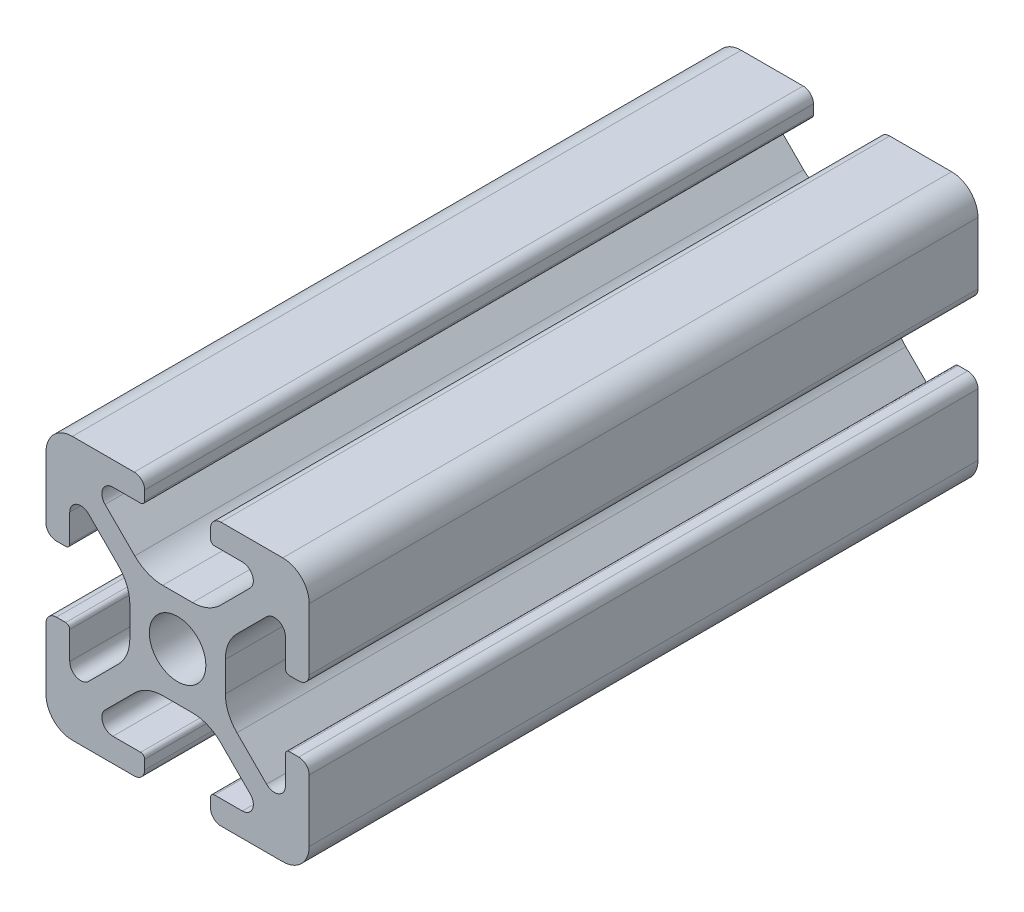
SolidWorks part; units mm, degrees
ref_plane "Front Plane" through (0, 0, 0) normal (0, 0, 1) x (1, 0, 0)
ref_plane "Top Plane" through (0, 0, 0) normal (0, 1, 0) x (1, 0, 0)
ref_plane "Right Plane" through (0, 0, 0) normal (1, 0, 0) x (0, 0, -1)
sketch "Sketch1" plane through (0, 0, 0) normal (0, 0, 1) x (1, 0, 0)
  line L2 (-9.9949, 7.9883) -> (-9.9949, 3.2893)
  line L3 (-7.9883, 9.9949) -> (-3.2893, 9.9949)
  line L4 (-2.5019, 9.2075) -> (-2.5019, 8.4963)
  line L5 (-2.8067, 8.1915) -> (-4.9149, 8.1915)
  line L6 (-5.5076, 6.7606) -> (-3.2528, 4.5058)
  line L7 (-6.7606, 5.5076) -> (-4.5058, 3.2528)
  line L8 (-8.1915, 4.9149) -> (-8.1915, 2.8067)
  line L9 (-8.4963, 2.5019) -> (-9.2075, 2.5019)
  line L11 (-1.1334, 3.6279) -> (1.1334, 3.6279)
  line L12 (-3.6279, 1.1334) -> (-3.6279, -1.1334)
  line L13 (8.4963, 2.5019) -> (9.2075, 2.5019)
  line L14 (8.1915, 4.9149) -> (8.1915, 2.8067)
  line L15 (9.9949, 7.9883) -> (9.9949, 3.2893)
  line L16 (7.9883, 9.9949) -> (3.2893, 9.9949)
  line L17 (2.5019, 9.2075) -> (2.5019, 8.4963)
  line L18 (2.8067, 8.1915) -> (4.9149, 8.1915)
  line L19 (3.6279, 1.1334) -> (3.6279, -1.1334)
  line L20 (5.5076, 6.7606) -> (3.2528, 4.5058)
  line L21 (6.7606, 5.5076) -> (4.5058, 3.2528)
  line L22 (-8.4963, -2.5019) -> (-9.2075, -2.5019)
  line L23 (-8.1915, -4.9149) -> (-8.1915, -2.8067)
  line L24 (-6.7606, -5.5076) -> (-4.5058, -3.2528)
  line L25 (-5.5076, -6.7606) -> (-3.2528, -4.5058)
  line L26 (-2.8067, -8.1915) -> (-4.9149, -8.1915)
  line L27 (-2.5019, -9.2075) -> (-2.5019, -8.4963)
  line L28 (-7.9883, -9.9949) -> (-3.2893, -9.9949)
  line L29 (-9.9949, -7.9883) -> (-9.9949, -3.2893)
  line L30 (9.9949, -7.9883) -> (9.9949, -3.2893)
  line L31 (7.9883, -9.9949) -> (3.2893, -9.9949)
  line L32 (2.5019, -9.2075) -> (2.5019, -8.4963)
  line L33 (2.8067, -8.1915) -> (4.9149, -8.1915)
  line L34 (5.5076, -6.7606) -> (3.2528, -4.5058)
  line L35 (6.7606, -5.5076) -> (4.5058, -3.2528)
  line L36 (8.1915, -4.9149) -> (8.1915, -2.8067)
  line L37 (8.4963, -2.5019) -> (9.2075, -2.5019)
  line L38 (-1.1334, -3.6279) -> (1.1334, -3.6279)
  circle A0 centre (0, 0) radius 2.1463
  arc A1 (-9.9949, 7.9883) -> (-7.9883, 9.9949) centre (-7.9883, 7.9883) cw
  arc A2 (-6.7606, 5.5076) -> (-8.1915, 4.9149) centre (-7.3533, 4.9149) ccw
  arc A3 (-4.9149, 8.1915) -> (-5.5076, 6.7606) centre (-4.9149, 7.3533) ccw
  arc A4 (-3.2893, 9.9949) -> (-2.5019, 9.2075) centre (-3.2893, 9.2075) cw
  arc A5 (-9.9949, 3.2893) -> (-9.2075, 2.5019) centre (-9.2075, 3.2893) ccw
  arc A6 (-8.1915, 2.8067) -> (-8.4963, 2.5019) centre (-8.4963, 2.8067) cw
  arc A7 (-2.5019, 8.4963) -> (-2.8067, 8.1915) centre (-2.8067, 8.4963) cw
  arc A8 (-1.1334, 3.6279) -> (-3.2528, 4.5058) centre (-1.1334, 6.6251) cw
  arc A9 (-3.6279, 1.1334) -> (-4.5058, 3.2528) centre (-6.6251, 1.1334) ccw
  arc A10 (8.1915, 2.8067) -> (8.4963, 2.5019) centre (8.4963, 2.8067) ccw
  arc A11 (9.9949, 3.2893) -> (9.2075, 2.5019) centre (9.2075, 3.2893) cw
  arc A12 (9.9949, 7.9883) -> (7.9883, 9.9949) centre (7.9883, 7.9883) ccw
  arc A13 (3.2893, 9.9949) -> (2.5019, 9.2075) centre (3.2893, 9.2075) ccw
  arc A14 (2.5019, 8.4963) -> (2.8067, 8.1915) centre (2.8067, 8.4963) ccw
  arc A15 (1.1334, 3.6279) -> (3.2528, 4.5058) centre (1.1334, 6.6251) ccw
  arc A16 (3.6279, 1.1334) -> (4.5058, 3.2528) centre (6.6251, 1.1334) cw
  arc A17 (6.7606, 5.5076) -> (8.1915, 4.9149) centre (7.3533, 4.9149) cw
  arc A18 (4.9149, 8.1915) -> (5.5076, 6.7606) centre (4.9149, 7.3533) cw
  arc A19 (-3.6279, -1.1334) -> (-4.5058, -3.2528) centre (-6.6251, -1.1334) cw
  arc A20 (-1.1334, -3.6279) -> (-3.2528, -4.5058) centre (-1.1334, -6.6251) ccw
  arc A21 (-2.5019, -8.4963) -> (-2.8067, -8.1915) centre (-2.8067, -8.4963) ccw
  arc A22 (-8.1915, -2.8067) -> (-8.4963, -2.5019) centre (-8.4963, -2.8067) ccw
  arc A23 (-9.9949, -3.2893) -> (-9.2075, -2.5019) centre (-9.2075, -3.2893) cw
  arc A24 (-3.2893, -9.9949) -> (-2.5019, -9.2075) centre (-3.2893, -9.2075) ccw
  arc A25 (-4.9149, -8.1915) -> (-5.5076, -6.7606) centre (-4.9149, -7.3533) cw
  arc A26 (-6.7606, -5.5076) -> (-8.1915, -4.9149) centre (-7.3533, -4.9149) cw
  arc A27 (-9.9949, -7.9883) -> (-7.9883, -9.9949) centre (-7.9883, -7.9883) ccw
  arc A28 (9.9949, -7.9883) -> (7.9883, -9.9949) centre (7.9883, -7.9883) cw
  arc A29 (6.7606, -5.5076) -> (8.1915, -4.9149) centre (7.3533, -4.9149) ccw
  arc A30 (4.9149, -8.1915) -> (5.5076, -6.7606) centre (4.9149, -7.3533) ccw
  arc A31 (3.2893, -9.9949) -> (2.5019, -9.2075) centre (3.2893, -9.2075) cw
  arc A32 (9.9949, -3.2893) -> (9.2075, -2.5019) centre (9.2075, -3.2893) ccw
  arc A33 (8.1915, -2.8067) -> (8.4963, -2.5019) centre (8.4963, -2.8067) cw
  arc A34 (2.5019, -8.4963) -> (2.8067, -8.1915) centre (2.8067, -8.4963) cw
  arc A35 (1.1334, -3.6279) -> (3.2528, -4.5058) centre (1.1334, -6.6251) cw
  arc A36 (3.6279, -1.1334) -> (4.5058, -3.2528) centre (6.6251, -1.1334) ccw
extrude "Boss-Extrude1" add sketch "Sketch1" along normal mid plane 50.8
